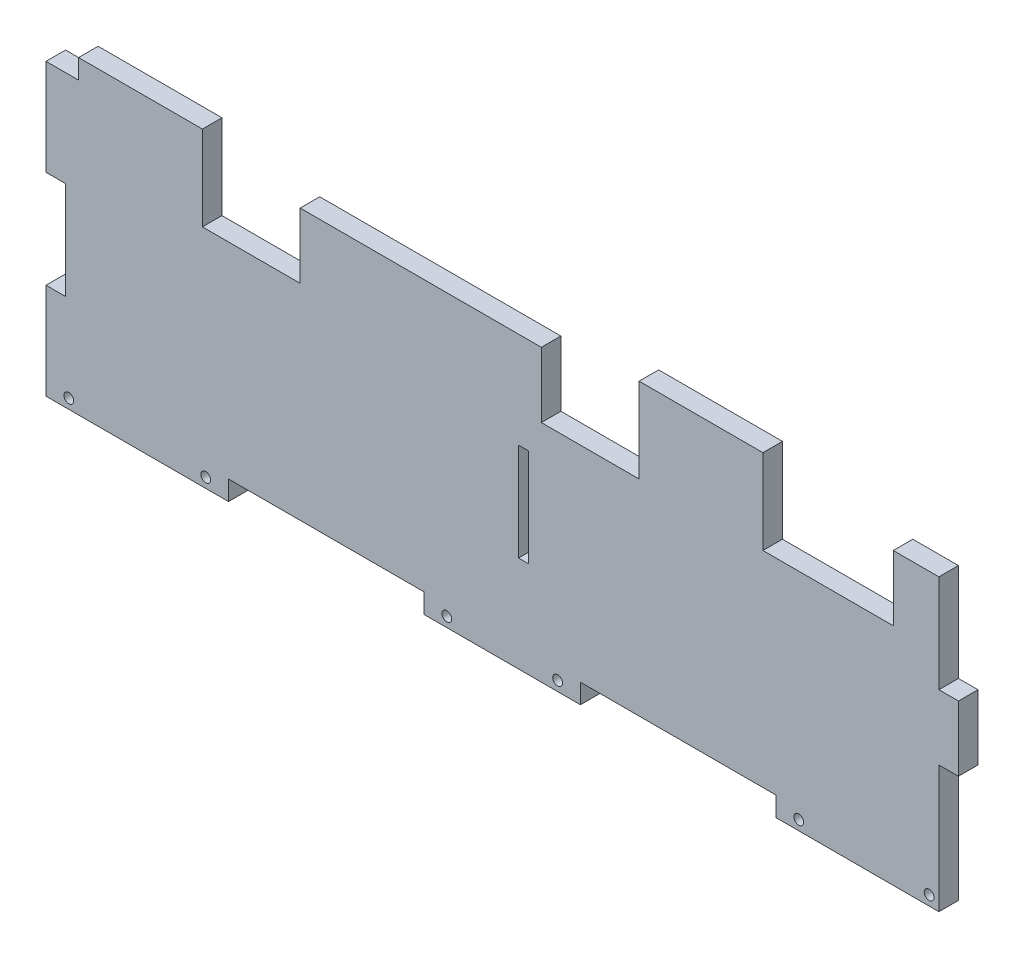
SolidWorks part; units mm, degrees
ref_plane "Plan de face" through (0, 0, 0) normal (0, 0, 1) x (1, 0, 0)
ref_plane "Plan de dessus" through (0, 0, 0) normal (0, 1, 0) x (1, 0, 0)
ref_plane "Plan de droite" through (0, 0, 0) normal (1, 0, 0) x (0, 0, -1)
sketch "Esquisse2" plane through (0, 0, 0) normal (0, 0, 1) x (1, 0, 0)
  line L1 (0, 0) -> (-330, 0)
  line L2 (0, 0) -> (0, 95)
  line L3 (0, 95) -> (-330, 95)
  line L4 (-330, 0) -> (-330, 95)
  dimension "D1" = 95
  dimension "D2" = 330
extrude "Boss.-Extru.1" add sketch "Esquisse2" along normal blind 6
sketch "Esquisse3" plane through (0, 0, 6) normal (0, 0, 1) x (1, 0, 0)
  line L0 (-330, 0) -> (0, 0) construction
  line L1 (-60, 95) -> (0, 95)
  line L2 (0, 95) -> (0, 59)
  line L3 (0, 59) -> (-6, 59)
  line L4 (-6, 89) -> (-6, 59)
  line L5 (0, 0) -> (-6, 0)
  line L6 (0, 0) -> (0, 39)
  line L7 (0, 39) -> (-6, 39)
  line L8 (-6, 0) -> (-6, 39)
  line L9 (-330, 95) -> (-270, 95)
  line L10 (0, 0) -> (0, 95) construction
  line L11 (-6, 89) -> (-20, 89)
  line L12 (-60, 95) -> (-60, 69)
  line L13 (-56, 0) -> (-116, 0)
  line L14 (-56, 0) -> (-56, 6)
  line L15 (-56, 6) -> (-116, 6)
  line L16 (-116, 0) -> (-116, 6)
  line L17 (0, 95) -> (-330, 95) construction
  line L18 (-164, 0) -> (-224, 0)
  line L19 (-164, 0) -> (-164, 6)
  line L20 (-164, 6) -> (-224, 6)
  line L21 (-224, 0) -> (-224, 6)
  line L22 (-280, 59.5) -> (-274, 59.5)
  line L23 (-280, 59.5) -> (-280, 29.5)
  line L24 (-280, 29.5) -> (-274, 29.5)
  line L25 (-274, 59.5) -> (-274, 29.5)
  line L26 (-20, 89) -> (-20, 69)
  line L27 (-330, 95) -> (-330, 59)
  line L28 (-330, 59) -> (-324, 59)
  line L29 (-324, 89) -> (-324, 59)
  line L30 (-330, 0) -> (-324, 0)
  line L31 (-330, 0) -> (-330, 39)
  line L32 (-330, 39) -> (-324, 39)
  line L33 (-324, 0) -> (-324, 39)
  line L34 (-98, 95) -> (-98, 69)
  line L35 (-128, 89) -> (-128, 69)
  line L36 (-324, 89) -> (-270, 89)
  line L37 (-270, 95) -> (-270, 89)
  line L38 (-232, 95) -> (-98, 95)
  line L39 (-232, 95) -> (-232, 69)
  line L40 (-202, 89) -> (-128, 89)
  line L41 (-20, 69) -> (-60, 69)
  line L42 (-128, 69) -> (-98, 69)
  line L43 (-135, 59.5) -> (-132, 59.5)
  line L44 (-135, 59.5) -> (-135, 29.5)
  line L45 (-135, 29.5) -> (-132, 29.5)
  line L46 (-132, 59.5) -> (-132, 29.5)
  line L50 (-232, 69) -> (-202, 69)
  line L51 (-202, 89) -> (-202, 69)
  dimension "D1" = 6
  dimension "D2" = 20
  dimension "D3" = 39
  dimension "D4" = 6
  dimension "D5" = 20
  dimension "D6" = 6
  dimension "D7" = 6
  dimension "D8" = 6
  dimension "D9" = 6
  dimension "D10" = 6
  dimension "D11" = 6
  dimension "D12" = 3
  dimension "D13" = 50
  dimension "D14" = 60
  dimension "D15" = 6
  dimension "D16" = 60
  dimension "D17" = 48
  dimension "D18" = 6
  dimension "D19" = 134
  dimension "D20" = 60
  dimension "D21" = 38
  dimension "D22" = 39
  dimension "D23" = 20
  dimension "D24" = 30
  dimension "D25" = 29.5
  dimension "D26" = 44
  dimension "D27" = 132
  dimension "D28" = 29.5
  dimension "D29" = 30
  dimension "D30" = 20
  dimension "D31" = 30
  dimension "D32" = 40
  dimension "D33" = 38
  dimension "D34" = 30
  dimension "D35" = 20
extrude "Enlèv. mat.-Extru.1" cut sketch "Esquisse3" against normal through all
sketch "Esquisse4" plane through (0, 0, 6) normal (0, 0, 1) x (1, 0, 0)
  line L0 (-324, 89) -> (-270, 89) construction
  line L1 (-280, 89) -> (-336.7992, 89)
  line L2 (-280, 89) -> (-280, 0)
  line L3 (-280, 0) -> (-336.7992, 0)
  line L4 (-336.7992, 89) -> (-336.7992, 0)
  line L5 (-280, 59.5) -> (-280, 29.5) construction
  line L6 (-324, 0) -> (-224, 0) construction
  dimension "D1" = 0
  dimension "D2" = 0
extrude "Enlèv. mat.-Extru.2" cut sketch "Esquisse4" against normal through all
sketch "Esquisse5" plane through (0, 0, 0) normal (0, 0, -1) x (-1, 0, 0)
  line L0 (280, 0) -> (280, 29.5) construction
  line L1 (280, 0) -> (224, 0) construction
  line L2 (224, 6) -> (224, 0) construction
  line L3 (116, 6) -> (116, 0) construction
  line L4 (164, 0) -> (116, 0) construction
  line L5 (164, 0) -> (164, 6) construction
  line L6 (56, 0) -> (56, 6) construction
  line L7 (56, 0) -> (6, 0) construction
  line L8 (6, 39) -> (6, 0) construction
  circle A0 centre (9, 3) radius 1.5
  circle A1 centre (49, 3) radius 1.5
  circle A2 centre (123, 3) radius 1.5
  circle A3 centre (157, 3) radius 1.5
  circle A4 centre (231, 3) radius 1.5
  circle A5 centre (273, 3) radius 1.5
  point P16 (224, 3)
  point P19 (116, 3)
  dimension "D1" = 3
  dimension "D2" = 7
  dimension "D3" = 3
  dimension "D4" = 3
  dimension "D5" = 7
  dimension "D6" = 3
  dimension "D7" = 3
  dimension "D8" = 7
  dimension "D9" = 3
  dimension "D10" = 3
  dimension "D12" = 3
  dimension "D13" = 3
  dimension "D14" = 7
  dimension "D15" = 3
  dimension "D16" = 3
  dimension "D17" = 3
  dimension "D18" = 3
  dimension "D11" = 7
extrude "Enlèv. mat.-Extru.3" cut sketch "Esquisse5" against normal through all
sketch "Esquisse6" plane through (0, 0, 0) normal (0, 0, -1) x (-1, 0, 0)
  circle A0 centre (9, 3) radius 2.995
  circle A1 centre (49, 3) radius 2.995
  circle A2 centre (123, 3) radius 2.995
  circle A3 centre (157, 3) radius 2.995
  circle A4 centre (273, 3) radius 2.995
  circle A5 centre (231, 3) radius 2.995
  dimension "D1" = 5.99
  dimension "D2" = 5.99
  dimension "D3" = 5.99
  dimension "D4" = 5.99
  dimension "D5" = 5.99
  dimension "D6" = 5.99
extrude "Enlèv. mat.-Extru.5" cut sketch "Esquisse6" against normal blind 3
